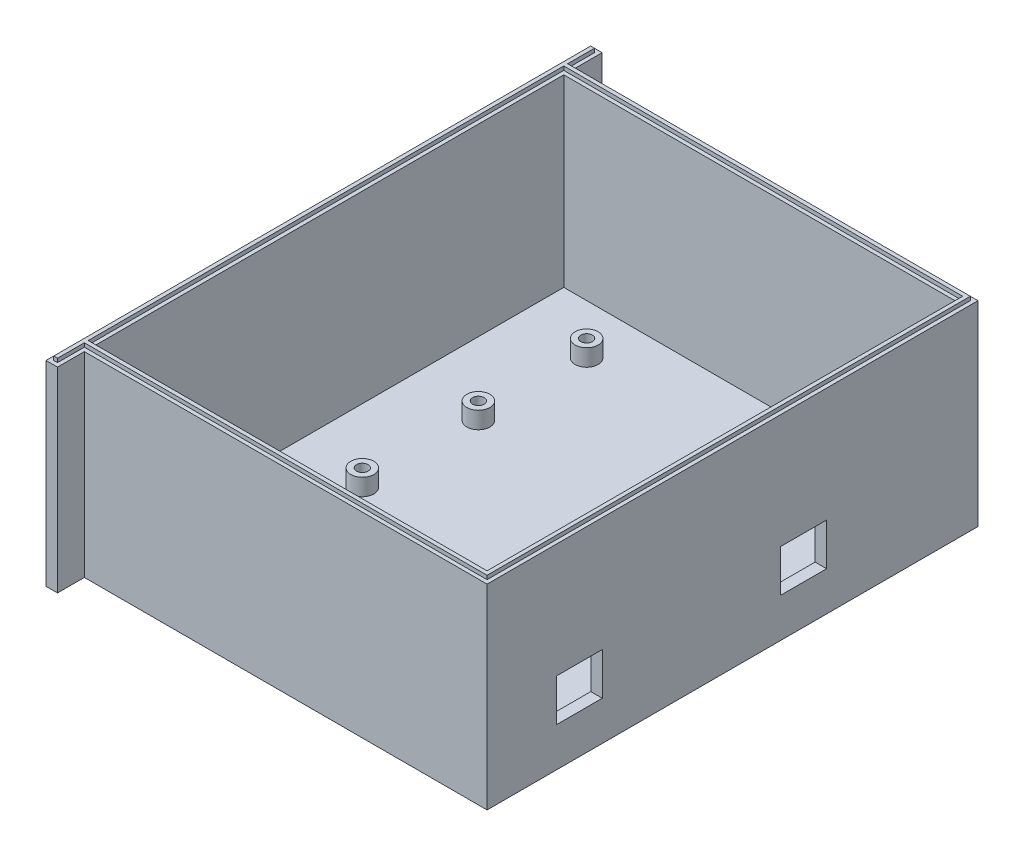
SolidWorks part; units mm, degrees
ref_plane "Plan de face" through (0, 0, 0) normal (0, 0, 1) x (1, 0, 0)
ref_plane "Plan de dessus" through (0, 0, 0) normal (0, 1, 0) x (1, 0, 0)
ref_plane "Plan de droite" through (0, 0, 0) normal (1, 0, 0) x (0, 0, -1)
sketch "Esquisse1" plane through (0, 0, 0) normal (0, 1, 0) x (1, 0, 0)
  line L0 (0, 0) -> (0, 142)
  line L1 (0, 142) -> (3, 142)
  line L2 (3, 142) -> (3, 135)
  line L3 (3, 135) -> (108, 135)
  line L4 (108, 135) -> (108, 7)
  line L5 (108, 7) -> (3, 7)
  line L6 (3, 7) -> (3, 0)
  line L7 (3, 0) -> (0, 0)
  dimension "D1" = 3
  dimension "D2" = 3
  dimension "D3" = 142
  dimension "D4" = 105
  dimension "D5" = 128
  dimension "D6" = 7
extrude "Boss.-Extru.1" add sketch "Esquisse1" along normal blind 51
sketch "Esquisse2" plane through (0, 51, 0) normal (0, 1, 0) x (1, 0, 0)
  line L0 (108, 135) -> (3, 135) construction
  line L1 (3, 132) -> (105, 132)
  line L2 (3, 132) -> (3, 10)
  line L3 (3, 10) -> (105, 10)
  line L4 (105, 132) -> (105, 10)
  line L5 (108, 7) -> (108, 135) construction
  line L6 (3, 7) -> (108, 7) construction
  line L7 (0, 142) -> (0, 0) construction
  dimension "D1" = 3
  dimension "D2" = 3
  dimension "D3" = 3
  dimension "D4" = 3
extrude "Enlèv. mat.-Extru.1" cut sketch "Esquisse2" against normal blind 48
sketch "Esquisse4" plane through (0, 51, 0) normal (0, 1, 0) x (1, 0, 0)
  line L0 (1, 1) -> (1, 141)
  line L1 (1, 1) -> (2, 1)
  line L2 (2, 1) -> (2, 8)
  line L3 (2, 8) -> (107, 8)
  line L4 (107, 8) -> (107, 134)
  line L5 (107, 134) -> (2, 134)
  line L6 (2, 134) -> (2, 141)
  line L7 (2, 141) -> (1, 141)
  line L8 (2, 133) -> (106, 133)
  line L9 (106, 133) -> (106, 9)
  line L10 (106, 9) -> (2, 9)
  line L14 (0, 0) -> (3, 0) construction
  line L15 (3, 0) -> (3, 7) construction
  line L16 (108, 135) -> (3, 135) construction
  line L17 (105, 132) -> (3, 132) construction
  line L21 (108, 7) -> (108, 135) construction
  line L22 (2, 133) -> (2, 9)
  line L23 (3, 7) -> (108, 7) construction
  line L24 (3, 10) -> (105, 10) construction
  dimension "D1" = 1
  dimension "D2" = 1
  dimension "D3" = 1
  dimension "D4" = 1
  dimension "D5" = 1
  dimension "D6" = 1
  dimension "D7" = 1
  dimension "D8" = 1
  dimension "D9" = 1
  dimension "D10" = 1
  dimension "D11" = 1
  dimension "D12" = 1
  dimension "D13" = 1
  dimension "D14" = 1
extrude "Boss.-Extru.4" add sketch "Esquisse4" along normal blind 1
sketch "Esquisse5" plane through (0, 3, 0) normal (0, 1, 0) x (1, 0, 0)
  line L0 (88.4, 132) -> (88.4, 10) construction
  line L1 (105, 132) -> (3, 132) construction
  line L2 (3, 10) -> (105, 10) construction
  line L3 (19.6, 132) -> (19.6, 10) construction
  line L4 (105, 10) -> (105, 132) construction
  line L5 (3, 132) -> (3, 10) construction
  line L6 (73.7, 17.456) -> (94.6583, 17.456) construction
  line L7 (73.7, 74.43) -> (94.6583, 74.43) construction
  circle A0 centre (74.7, 124.56) radius 1.5
  circle A1 centre (74.7, 124.56) radius 3
  circle A2 centre (73.7, 74.43) radius 1.5
  circle A3 centre (73.7, 74.43) radius 3
  circle A4 centre (21.9, 32.346) radius 1.5
  circle A5 centre (21.9, 32.346) radius 3
  circle A6 centre (73.7, 17.456) radius 1.5
  circle A7 centre (73.7, 17.456) radius 3
  circle A8 centre (21.9, 60.576) radius 1.5
  circle A9 centre (21.9, 60.576) radius 3
  circle A10 centre (21.9, 119.06) radius 1.5
  circle A11 centre (21.9, 119.06) radius 3
  circle A12 centre (74.7, 66.086) radius 1.5
  circle A13 centre (74.7, 66.086) radius 3
  circle A14 centre (21.9, 90.83) radius 1.5
  circle A15 centre (21.9, 90.83) radius 3
  dimension "D4" = 3
  dimension "D5" = 6
  dimension "D6" = 3
  dimension "D7" = 6
  dimension "D8" = 6
  dimension "D9" = 3
  dimension "D10" = 6
  dimension "D11" = 3
  dimension "D12" = 6
  dimension "D13" = 3
  dimension "D14" = 3
  dimension "D15" = 6
  dimension "D16" = 6
  dimension "D17" = 3
  dimension "D19" = 22.346
  dimension "D20" = 3
  dimension "D21" = 6
  dimension "D1" = 68.8
  dimension "D2" = 16.6
  dimension "D3" = 16.6
  dimension "D18" = 7.456
  dimension "D22" = 14.7
  dimension "D23" = 66.5
  dimension "D24" = 13.7
  dimension "D25" = 13.7
  dimension "D26" = 14.7
  dimension "D27" = 48.63
  dimension "D28" = 66.5
  dimension "D29" = 48.63
  dimension "D30" = 7.44
  dimension "D31" = 28.23
  dimension "D32" = 12.94
  dimension "D33" = 28.23
  dimension "D34" = 66.5
  dimension "D35" = 66.5
extrude "Boss.-Extru.5" add sketch "Esquisse5" along normal blind 4.41
sketch "Esquisse7" plane through (108, 0, 0) normal (1, 0, 0) x (0, 0, -1)
  line L0 (7, 0) -> (135, 0) construction
  line L1 (25.04, 21.21) -> (37.04, 21.21)
  line L2 (25.04, 21.21) -> (25.04, 10.21)
  line L3 (25.04, 10.21) -> (37.04, 10.21)
  line L4 (37.04, 21.21) -> (37.04, 10.21)
  line L5 (83.53, 21.21) -> (95.53, 21.21)
  line L6 (83.53, 21.21) -> (83.53, 10.21)
  line L7 (83.53, 10.21) -> (95.53, 10.21)
  line L8 (95.53, 21.21) -> (95.53, 10.21)
  line L9 (135, 51) -> (135, 0) construction
  line L10 (7, 51) -> (7, 0) construction
  dimension "D1" = 12
  dimension "D2" = 12
  dimension "D3" = 11
  dimension "D4" = 11
  dimension "D5" = 21.21
  dimension "D6" = 21.21
  dimension "D7" = 39.47
  dimension "D8" = 18.04
extrude "Enlèv. mat.-Extru.2" cut sketch "Esquisse7" against normal blind 3
sketch "Esquisse8" plane through (108, 0, 0) normal (1, 0, 0) x (0, 0, -1)
  line L0 (7, 0) -> (135, 0) construction
  line L1 (11.27, 3) -> (23.77, 3)
  line L2 (11.27, 3) -> (11.27, 34.9)
  line L3 (11.27, 34.9) -> (23.77, 34.9)
  line L4 (23.77, 3) -> (23.77, 34.9)
  line L5 (43.036, 3) -> (55.536, 3)
  line L6 (43.036, 3) -> (43.036, 34.9)
  line L7 (43.036, 34.9) -> (55.536, 34.9)
  line L8 (55.536, 3) -> (55.536, 34.9)
  line L9 (60.2015, 3) -> (72.7015, 3)
  line L10 (60.2015, 3) -> (60.2015, 34.9)
  line L11 (60.2015, 34.9) -> (72.7015, 34.9)
  line L12 (72.7015, 3) -> (72.7015, 34.9)
  line L13 (73.5984, 3) -> (86.0984, 3)
  line L14 (73.5984, 3) -> (73.5984, 34.9)
  line L15 (73.5984, 34.9) -> (86.0984, 34.9)
  line L16 (86.0984, 3) -> (86.0984, 34.9)
  line L17 (104.1982, 3) -> (116.6982, 3)
  line L18 (104.1982, 3) -> (104.1982, 34.9)
  line L19 (104.1982, 34.9) -> (116.6982, 34.9)
  line L20 (116.6982, 3) -> (116.6982, 34.9)
  line L21 (118.23, 3) -> (130.73, 3)
  line L22 (118.23, 3) -> (118.23, 34.9)
  line L23 (118.23, 34.9) -> (130.73, 34.9)
  line L24 (130.73, 3) -> (130.73, 34.9)
  line L25 (11.27, 50.432) -> (43.17, 50.432)
  line L26 (11.27, 50.432) -> (11.27, 37.932)
  line L27 (11.27, 37.932) -> (43.17, 37.932)
  line L28 (43.17, 50.432) -> (43.17, 37.932)
  line L29 (47.9879, 50.432) -> (79.8879, 50.432)
  line L30 (47.9879, 50.432) -> (47.9879, 37.932)
  line L31 (47.9879, 37.932) -> (79.8879, 37.932)
  line L32 (79.8879, 50.432) -> (79.8879, 37.932)
  line L33 (98.83, 50.432) -> (130.73, 50.432)
  line L34 (98.83, 50.432) -> (98.83, 37.932)
  line L35 (98.83, 37.932) -> (130.73, 37.932)
  line L36 (130.73, 50.432) -> (130.73, 37.932)
  line L37 (7, 51) -> (7, 0) construction
  line L38 (135, 51) -> (135, 0) construction
  dimension "D1" = 12.5
  dimension "D2" = 12.5
  dimension "D3" = 12.5
  dimension "D4" = 12.5
  dimension "D5" = 12.5
  dimension "D6" = 12.5
  dimension "D7" = 12.5
  dimension "D8" = 12.5
  dimension "D9" = 12.5
  dimension "D10" = 31.9
  dimension "D11" = 31.9
  dimension "D12" = 31.9
  dimension "D13" = 31.9
  dimension "D14" = 31.9
  dimension "D15" = 31.9
  dimension "D16" = 3
  dimension "D17" = 3
  dimension "D18" = 3
  dimension "D19" = 3
  dimension "D20" = 3
  dimension "D21" = 3
  dimension "D22" = 31.9
  dimension "D23" = 31.9
  dimension "D24" = 31.9
  dimension "D25" = 4.27
  dimension "D26" = 4.27
  dimension "D27" = 4.27
  dimension "D28" = 4.27
